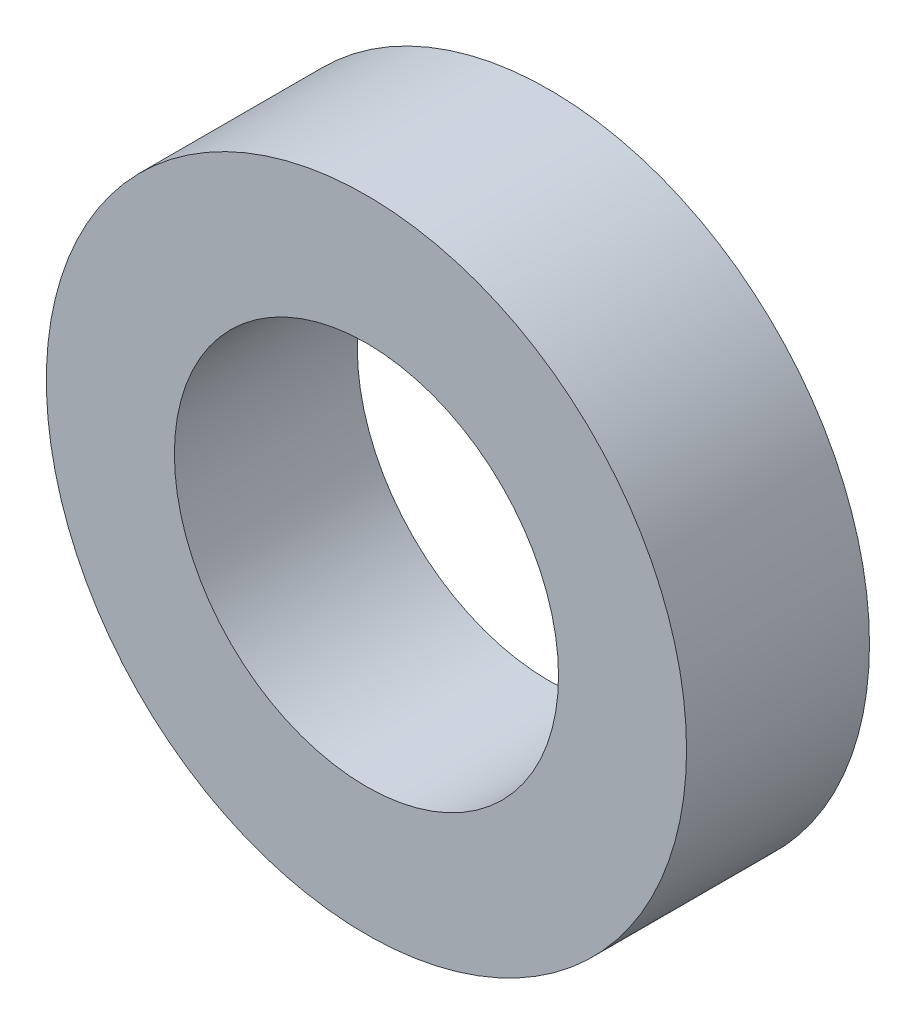
SolidWorks part; units mm, degrees
ref_plane "前视基准面" through (0, 0, 0) normal (0, 0, 1) x (1, 0, 0)
ref_plane "上视基准面" through (0, 0, 0) normal (0, 1, 0) x (1, 0, 0)
ref_plane "右视基准面" through (0, 0, 0) normal (1, 0, 0) x (0, 0, -1)
sketch "草图1" plane through (0, 0, 0) normal (0, 0, 1) x (1, 0, 0)
  circle A0 centre (0, 0) radius 3.5
  circle A1 centre (0, 0) radius 2.1
  dimension "D1" = 7
  dimension "D2" = 4.2
extrude "凸台-拉伸1" add sketch "草图1" along normal blind 2 contours A0
